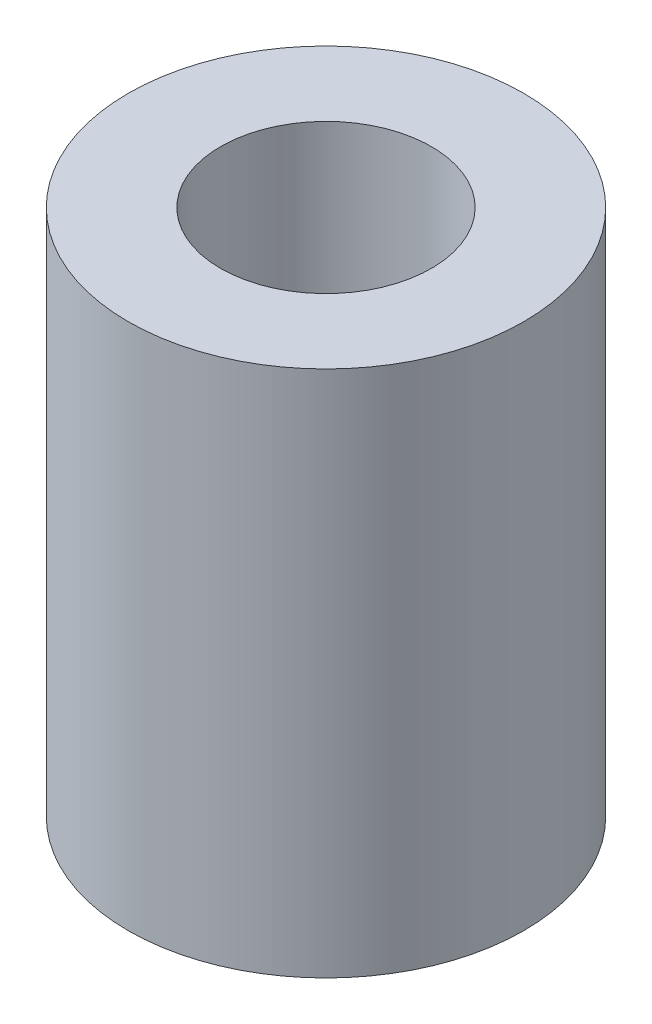
SolidWorks part; units mm, degrees
material "1060 합금"
ref_plane "정면" through (0, 0, 0) normal (0, 0, 1) x (1, 0, 0)
ref_plane "윗면" through (0, 0, 0) normal (0, 1, 0) x (1, 0, 0)
ref_plane "우측면" through (0, 0, 0) normal (1, 0, 0) x (0, 0, -1)
sketch "스케치1" plane through (0, 0, 0) normal (0, 1, 0) x (1, 0, 0)
  circle A0 centre (0, 0) radius 7.5
  dimension "D1" = 15
extrude "보스-돌출1" add sketch "스케치1" against normal blind 20
sketch "스케치3" plane through (0, 0, 0) normal (0, 1, 0) x (1, 0, 0)
  circle A0 centre (0, 0) radius 4
  dimension "D1" = 8
extrude "컷-돌출1" cut sketch "스케치3" against normal blind 21.36
